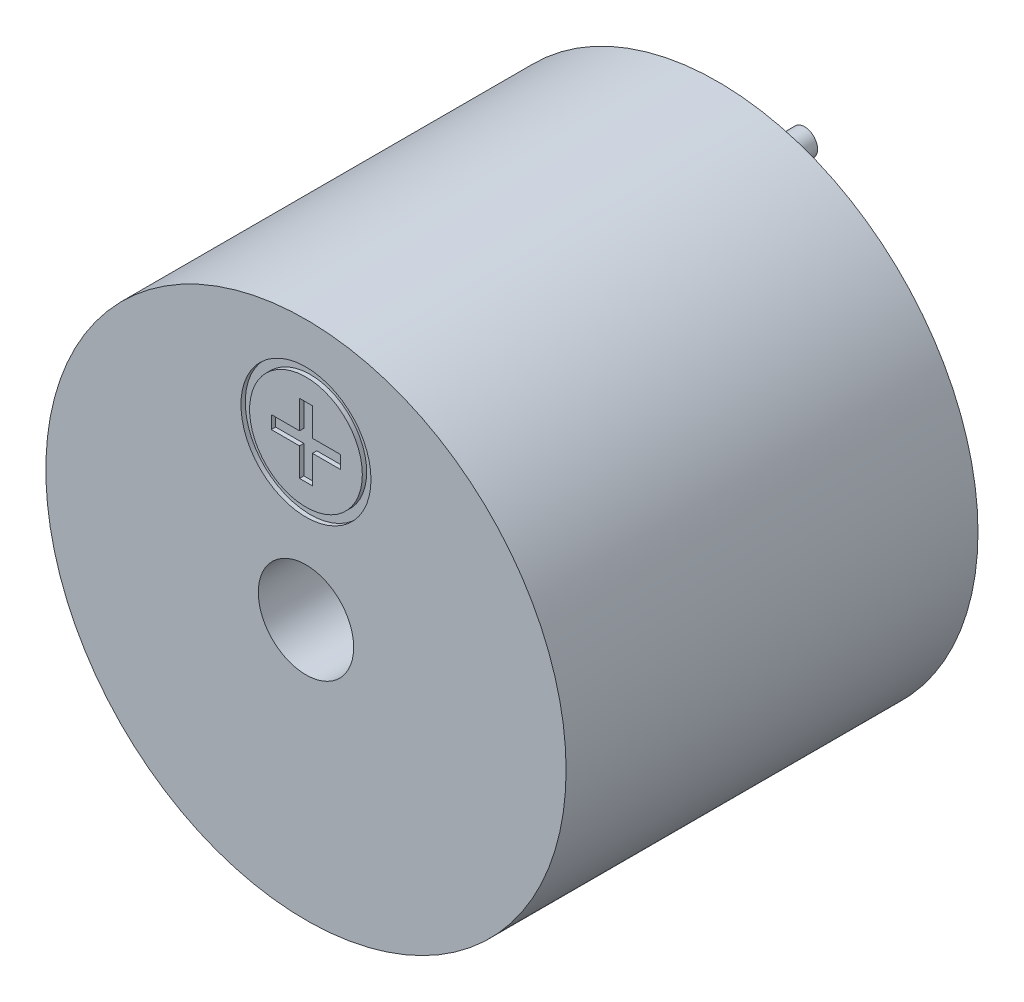
SolidWorks part; units mm, degrees
ref_plane "Front Plane" through (0, 0, 0) normal (0, 0, 1) x (1, 0, 0)
ref_plane "Top Plane" through (0, 0, 0) normal (0, 1, 0) x (1, 0, 0)
ref_plane "Right Plane" through (0, 0, 0) normal (1, 0, 0) x (0, 0, -1)
sketch "Sketch1" plane through (0, 0, 0) normal (0, 0, 1) x (1, 0, 0)
  circle A0 centre (0, 0) radius 6
extrude "Boss-Extrude2" add sketch "Sketch1" along normal blind 3 contours A0
sketch "Sketch4" plane through (0, 0, 3) normal (0, 0, 1) x (1, 0, 0)
  circle A0 centre (0, 0) radius 6
  circle A1 centre (0, 0) radius 6
extrude "Boss-Extrude3" add sketch "Sketch4" along normal blind 6.5 contours A1
sketch "Sketch5" plane through (0, 0, 9.5) normal (0, 0, 1) x (1, 0, 0)
  circle A0 centre (0, 0) radius 1.1
extrude "Cut-Extrude2" cut sketch "Sketch5" against normal blind 6.5
sketch "Sketch6" plane through (0, 0, 9.5) normal (0, 0, 1) x (1, 0, 0)
  line L1 (0.8, 3.55) -> (0.8, 3.7)
  line L2 (0.8, 3.55) -> (0.8, 3.4)
  line L3 (0.8, 3.4) -> (0.15, 3.4)
  line L4 (0.8, 3.7) -> (0.15, 3.7)
  line L5 (0.15, 3.7) -> (0.15, 4.35)
  line L6 (0.15, 4.35) -> (-0.15, 4.35)
  line L7 (-0.15, 4.35) -> (-0.15, 3.7)
  line L8 (-0.15, 3.7) -> (-0.8, 3.7)
  line L9 (-0.8, 3.7) -> (-0.8, 3.4)
  line L10 (-0.8, 3.4) -> (-0.15, 3.4)
  line L11 (-0.15, 3.4) -> (-0.15, 2.75)
  line L12 (-0.15, 2.75) -> (0.15, 2.75)
  line L13 (0.15, 2.75) -> (0.15, 3.4)
  circle A1 centre (0, 3.55) radius 1.5
  circle A2 centre (0, 3.55) radius 1.3
extrude "Cut-Extrude3" cut sketch "Sketch6" against normal blind 0.1 contours L12 L13 L3 L2 L1 L4 L5 L6 L7 L8 L9 L10 L11 | A1 A2
sketch "Sketch7" plane through (0, 0, 0) normal (0, 0, -1) x (-1, 0, 0)
  line L5 (0, 5.225) -> (0, -5.225) construction
  circle A0 centre (0, 3.8) radius 0.3
  circle A1 centre (0, -3.8) radius 0.3
extrude "Boss-Extrude4" add sketch "Sketch7" along normal blind 2
